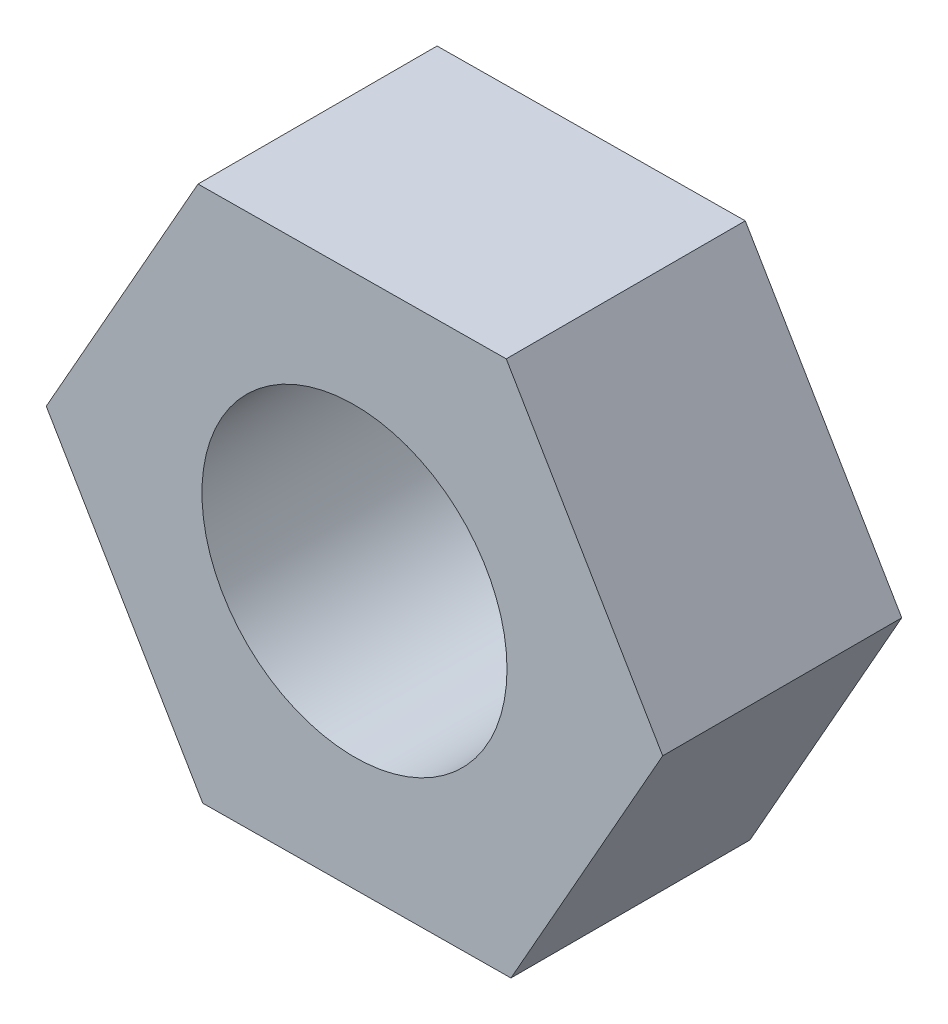
SolidWorks part; units mm, degrees
ref_plane "前视基准面" through (0, 0, 0) normal (0, 0, 1) x (1, 0, 0)
ref_plane "上视基准面" through (0, 0, 0) normal (0, 1, 0) x (1, 0, 0)
ref_plane "右视基准面" through (0, 0, 0) normal (1, 0, 0) x (0, 0, -1)
sketch "草图1" plane through (0, 0, 0) normal (0, 0, 1) x (1, 0, 0)
  line L1 (1.9635, -3.3328) -> (3.8681, 0.0341)
  line L2 (3.8681, 0.0341) -> (1.9046, 3.3669)
  line L3 (1.9046, 3.3669) -> (-1.9635, 3.3328)
  line L4 (-1.9635, 3.3328) -> (-3.8681, -0.0341)
  line L5 (-3.8681, -0.0341) -> (-1.9046, -3.3669)
  line L6 (-1.9046, -3.3669) -> (1.9635, -3.3328)
  circle A0 centre (0, 0) radius 3.35 construction
  circle A1 centre (0, 0) radius 1.9143
  dimension "D1" = 6.7
extrude "凸台-拉伸1" add sketch "草图1" along normal blind 3
